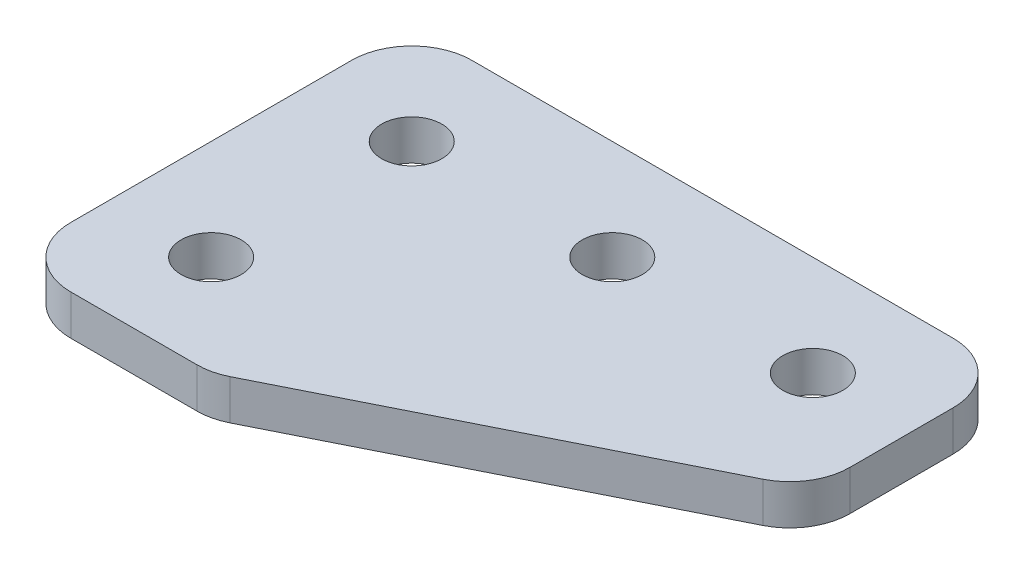
SolidWorks part; units mm, degrees
ref_plane "前视基准面" through (0, 0, 0) normal (0, 0, 1) x (1, 0, 0)
ref_plane "上视基准面" through (0, 0, 0) normal (0, 1, 0) x (1, 0, 0)
ref_plane "右视基准面" through (0, 0, 0) normal (1, 0, 0) x (0, 0, -1)
other "Configuration Table"
sketch "草图1" plane through (0, 0, 0) normal (0, 1, 0) x (1, 0, 0)
  line L0 (0, 10) -> (-10, 10)
  line L1 (0, 0) -> (20, 0) construction
  line L2 (0, 0) -> (0, 10) construction
  line L3 (0, 10) -> (20, 10)
  line L4 (20, 0) -> (20, 10)
  line L5 (0, 0) -> (-10, 0) construction
  line L9 (-10, 10) -> (-10, 0)
  line L10 (-10, 0) -> (-10, -10)
  line L11 (-10, 5) -> (20, 5) construction
  line L12 (-5, 10) -> (-5, -10) construction
  line L13 (-10, -10) -> (0, -10)
  line L14 (0, -10) -> (20, 0)
  circle A1 centre (5, 5) radius 1.5
  circle A2 centre (15, 5) radius 1.5
  circle A3 centre (-5, 5) radius 1.5
  circle A4 centre (-5, -5) radius 1.5
  dimension "D7" = 3
  dimension "D1" = 10
  dimension "D2" = 20
  dimension "D3" = 10
  dimension "D4" = 10
  dimension "D5" = 10
  dimension "D6" = 10
extrude "凸台-拉伸1" add sketch "草图1" along normal blind 2
fillet "圆角1" radius 3 5 edges at (-10, 1, -10) (20, 1, -10) (20, 1, 0) (0, 1, 10) (-10, 1, 10)
